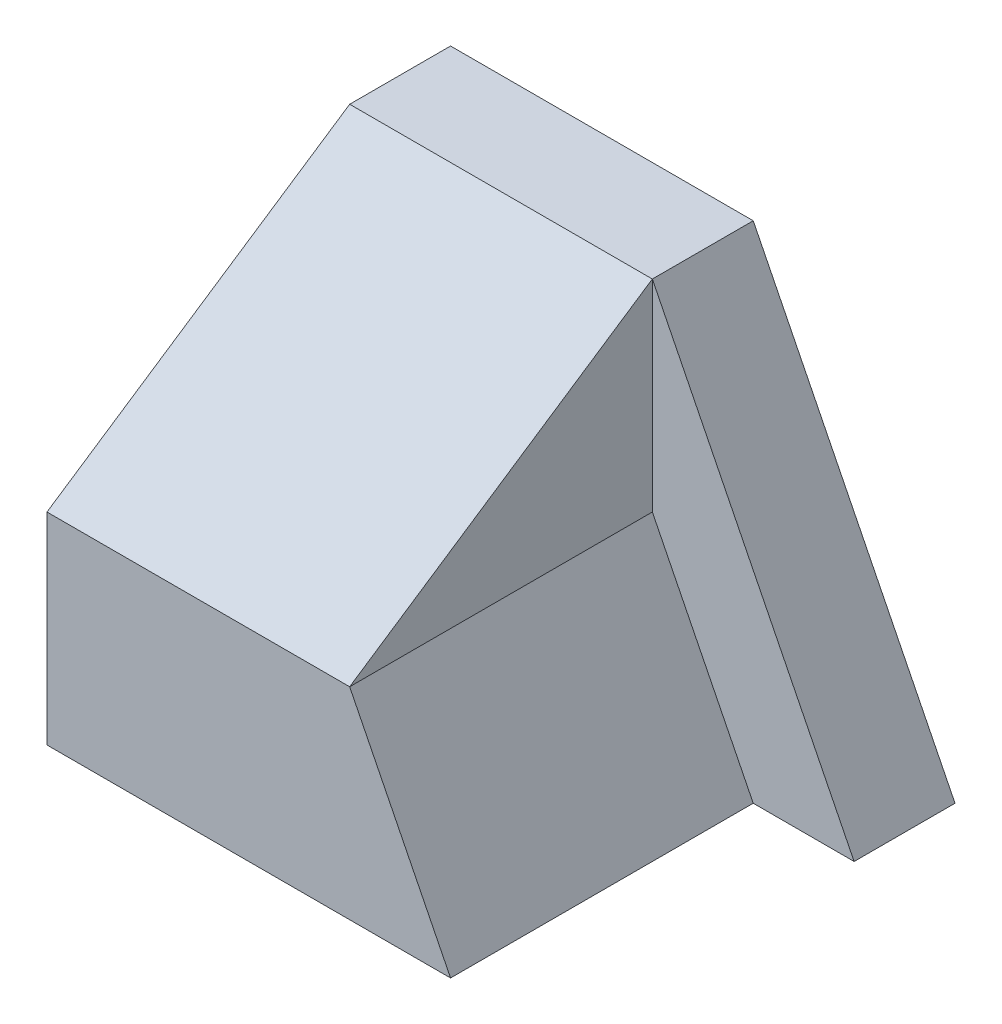
SolidWorks part; units mm, degrees
ref_plane "Front Plane" through (0, 0, 0) normal (0, 0, 1) x (1, 0, 0)
ref_plane "Top Plane" through (0, 0, 0) normal (0, 1, 0) x (1, 0, 0)
ref_plane "Right Plane" through (0, 0, 0) normal (1, 0, 0) x (0, 0, -1)
sketch "Sketch1" plane through (0, 0, 0) normal (0, 1, 0) x (1, 0, 0)
  line L1 (0, 0) -> (3, 0)
  line L2 (0, 0) -> (0, 1)
  line L3 (0, 1) -> (3, 1)
  line L4 (3, 0) -> (3, 1)
  dimension "D1" = 1
  dimension "D2" = 3
extrude "Boss-Extrude1" add sketch "Sketch1" along normal blind 4 contours L3 L4 L1 L2
sketch "Sketch2" plane through (0, 0, 0) normal (0, -1, 0) x (1, 0, 0)
  line L0 (3, -1) -> (5, -1)
  line L1 (5, -1) -> (5, 0)
  line L2 (5, 0) -> (3, 0)
  line L3 (3, 0) -> (3, -1)
  line L7 (0, 0) -> (0, -1)
  line L8 (0, -1) -> (3, -1)
  line L9 (3, -1) -> (3, 0)
  line L10 (3, 0) -> (0, 0)
  line L13 (3, -1) -> (3, 0)
  point P8 (0, 0)
  point P9 (0, 0)
  point P10 (0, 0)
  point P11 (0, 0)
  point P12 (0, 0)
  point P13 (0, 0)
  point P14 (0, 0)
  point P15 (0, 0)
  point P16 (0, 0)
  point P17 (0, 0)
  point P18 (0, 0)
  point P19 (0, 0)
  point P20 (0, 0)
  point P21 (0, 0)
  point P22 (0, 0)
  point P23 (0, 0)
  line M5 (3, -1) -> (3, 0)
  dimension "D1" = 2
  dimension "D2" = 2
  dimension "D3" = 0
extrude "Boss-Extrude3" add sketch "Sketch2" against normal blind 4 separate body contours L1 L2 L0 M5
sketch "Sketch3" plane through (0, 0, 0) normal (0, 0, 1) x (1, 0, 0)
  line L0 (3, 4) -> (5, 0)
  line L1 (3, 4) -> (5, 4)
  line L2 (5, 4) -> (3, 4) construction
  line L3 (5, 4) -> (5, 0)
extrude "Cut-Extrude3" cut sketch "Sketch3" against normal blind 4
sketch "Sketch4" plane through (0, 0, 0) normal (0, 0, 1) x (1, 0, 0)
  line L0 (0, 0) -> (4, 0)
  line L1 (5, 0) -> (3, 0) construction
  line L2 (0, 0) -> (0, 2)
  line L3 (0, 4) -> (0, 0) construction
  line L4 (0, 2) -> (3, 2)
  line L5 (3, 4) -> (3, 0) construction
  line L6 (3, 2) -> (4, 0)
extrude "Boss-Extrude4" add sketch "Sketch4" along normal blind 3
sketch "Sketch5" plane through (0, 0, 0) normal (0, 0, 1) x (1, 0, 0)
  line L0 (0, 2) -> (0, 4)
  line L1 (0, 4) -> (3, 4)
  line L2 (3, 4) -> (3, 2)
  line L3 (3, 2) -> (0, 2)
extrude "Boss-Extrude6" add sketch "Sketch5" along normal blind 3 separate body
sketch "Sketch6" plane through (3, 0, 0) normal (1, 0, 0) x (0, 0, -1)
  line L0 (-3, 2) -> (0, 4)
  line L1 (0, 4) -> (-3, 4)
  line L2 (-3, 4) -> (-3, 2)
  line L3 (-3, 2) -> (-3.0603, 1.9586)
  line M2 (0, 4) -> (-3, 4)
  line M3 (-3, 4) -> (-3, 2)
extrude "Cut-Extrude4" cut sketch "Sketch6" against normal blind 3 contours L0 M3 M2
